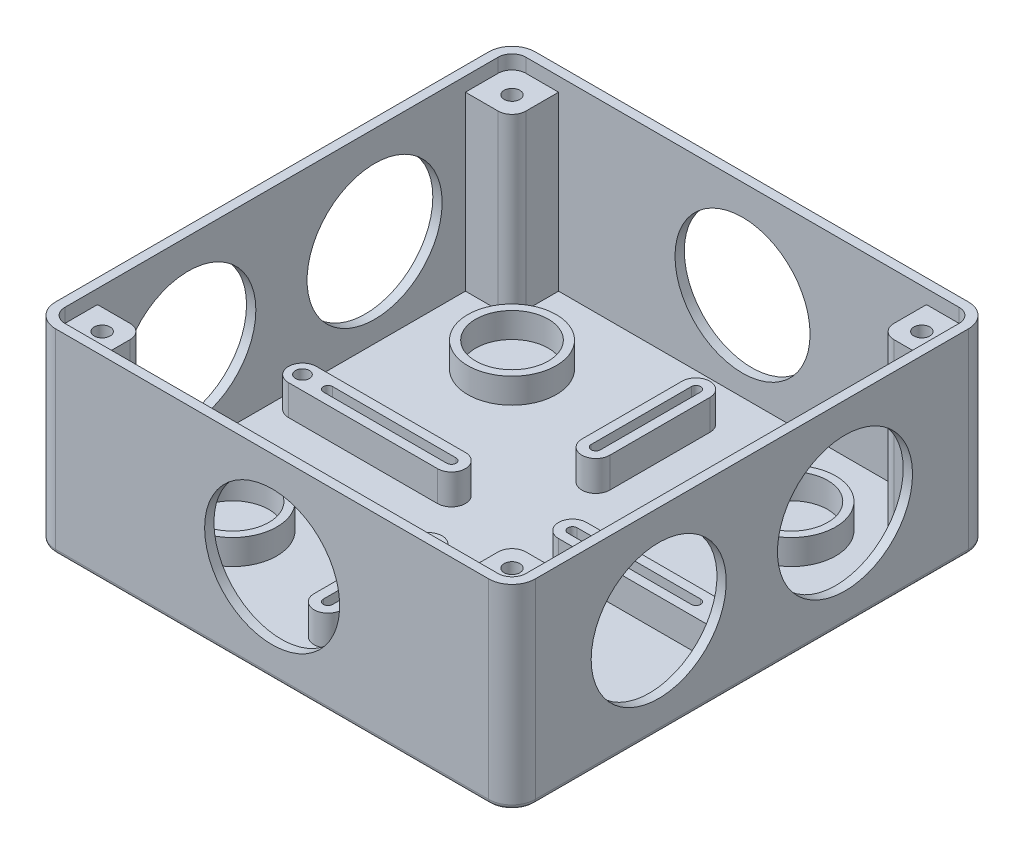
SolidWorks part; units mm, degrees
material "PBT General Purpose"
ref_plane "Front Plane" through (0, 0, 0) normal (0, 0, 1) x (1, 0, 0)
ref_plane "Top Plane" through (0, 0, 0) normal (0, 1, 0) x (1, 0, 0)
ref_plane "Right Plane" through (0, 0, 0) normal (1, 0, 0) x (0, 0, -1)
sketch "Sketch1" plane through (0, 0, 0) normal (0, 1, 0) x (1, 0, 0)
  line L0 (0, 51.5) -> (0, 0) construction
  line L1 (0, 0) -> (51.5, 0) construction
  line L2 (51.5, -46.5) -> (51.5, 46.5)
  line L3 (46.5, 51.5) -> (-46.5, 51.5)
  line L4 (-51.5, -46.5) -> (-51.5, 46.5)
  line L5 (46.5, -51.5) -> (-46.5, -51.5)
  arc A0 (51.5, 46.5) -> (46.5, 51.5) centre (46.5, 46.5) ccw
  arc A1 (-51.5, 46.5) -> (-46.5, 51.5) centre (-46.5, 46.5) cw
  arc A2 (-51.5, -46.5) -> (-46.5, -51.5) centre (-46.5, -46.5) ccw
  arc A3 (51.5, -46.5) -> (46.5, -51.5) centre (46.5, -46.5) cw
  point P17 (-51.5, 0)
  dimension "D1" = 5
  dimension "D2" = 103
  dimension "D3" = 103
extrude "Boss-Extrude1" add sketch "Sketch1" along normal blind 42
fillet "Fillet1" radius 1 8 edges at (-50.0355, 0, 50.0355) (-51.5, 0, 0) (-50.0355, 0, -50.0355) (0, 0, -51.5) (50.0355, 0, -50.0355) (51.5, 0, 0) (50.0355, 0, 50.0355) (0, 0, 51.5)
shell "Shell1" thickness 2
sketch "Sketch2" plane through (0, 0, 0) normal (0, -1, 0) x (1, 0, 0)
  line L0 (0, 64.6316) -> (0, 0) construction
  line L1 (0, 0) -> (65.5067, 0) construction
  line L2 (30, 39) -> (-30, 39)
  line L3 (30, -39) -> (-30, -39)
  line L4 (39, 30) -> (39, -30)
  line L5 (-39, 30) -> (-39, -30)
  line L6 (24.3431, 37) -> (-24.3431, 37)
  line L7 (24.3431, -37) -> (-24.3431, -37)
  line L8 (37, 24.3431) -> (37, -24.3431)
  line L9 (-37, 24.3431) -> (-37, -24.3431)
  line L11 (30, 37) -> (-30, 37) construction
  line L12 (37, 30) -> (37, -30) construction
  circle A0 centre (30, 30) radius 4
  arc A1 (39, 30) -> (30, 39) centre (30, 30) ccw
  arc A2 (24.3431, -37) -> (37, -24.3431) centre (30, -30) cw
  circle A3 centre (30, -30) radius 4
  circle A4 centre (-30, -30) radius 4
  arc A5 (-39, -30) -> (-30, -39) centre (-30, -30) ccw
  arc A6 (-24.3431, 37) -> (-37, 24.3431) centre (-30, 30) cw
  circle A7 centre (-30, 30) radius 4
  arc A8 (-39, 30) -> (-30, 39) centre (-30, 30) cw
  arc A9 (-24.3431, -37) -> (-37, -24.3431) centre (-30, -30) ccw
  arc A10 (39, -30) -> (30, -39) centre (30, -30) cw
  arc A11 (24.3431, 37) -> (37, 24.3431) centre (30, 30) ccw
  dimension "D1" = 8
  dimension "D2" = 18
  dimension "D3" = 60
  dimension "D4" = 60
  dimension "D7" = 2
  dimension "D8" = 2
  dimension "D5" = 2
  dimension "D6" = 2
extrude "Boss-Extrude2" add sketch "Sketch2" along normal blind 1.2
sketch "Sketch3" plane through (0, 0, -51.5) normal (0, 0, -1) x (-1, 0, 0)
  line L0 (0, 0) -> (0, 69.3908) construction
  line L1 (-46.5, 42) -> (46.5, 42) construction
  circle A0 centre (-42.5, 21) radius 14.5 construction
  circle A1 centre (0, 21) radius 14.5
  circle A2 centre (42.5, 21) radius 14.5 construction
  dimension "D1" = 29
  dimension "D2" = 6.5
extrude "Cut-Extrude1" cut sketch "Sketch3" against normal through all
sketch "Sketch4" plane through (0, 0, 0) normal (1, 0, 0) x (0, 0, -1)
  line L0 (0, 0) -> (0, 62.8314) construction
  line L1 (-46.5, 42) -> (46.5, 42) construction
  circle A0 centre (20, 21) radius 14.5
  circle A1 centre (-20, 21) radius 14.5
  dimension "D1" = 29
  dimension "D2" = 11
  dimension "D3" = 6.5
extrude "Cut-Extrude2" cut sketch "Sketch4" against normal through all and the other way through all
sketch "Sketch5" plane through (0, 0, 0) normal (0, -1, 0) x (1, 0, 0)
  line L0 (-22.35, 22.35) -> (22.35, 22.35)
  line L1 (-9.5, -9.5) -> (9.5, -9.5)
  line L2 (-9.5, -9.5) -> (-9.5, 9.5)
  line L3 (-9.5, 9.5) -> (9.5, 9.5)
  line L4 (9.5, -9.5) -> (9.5, 9.5)
  line L5 (-9.5, -9.5) -> (9.5, 9.5) construction
  line L6 (-9.5, 9.5) -> (9.5, -9.5) construction
  line L7 (-24.35, -24.35) -> (24.35, -24.35)
  line L8 (-24.35, -24.35) -> (-24.35, 24.35)
  line L9 (-24.35, 24.35) -> (24.35, 24.35)
  line L10 (24.35, -24.35) -> (24.35, 24.35)
  line L11 (-24.35, -24.35) -> (24.35, 24.35) construction
  line L12 (-24.35, 24.35) -> (24.35, -24.35) construction
  line L13 (22.35, -22.35) -> (22.35, 22.35)
  line L14 (-22.35, -22.35) -> (22.35, -22.35)
  line L15 (-22.35, -22.35) -> (-22.35, 22.35)
  line L16 (-7.5, 7.5) -> (7.5, 7.5)
  line L17 (7.5, -7.5) -> (7.5, 7.5)
  line L18 (-7.5, -7.5) -> (7.5, -7.5)
  line L19 (-7.5, -7.5) -> (-7.5, 7.5)
  point P0 (0, 0)
  point P6 (0, 0)
  dimension "D1" = 48.7
  dimension "D3" = 19
  dimension "D5" = 2
extrude "Boss-Extrude3" add sketch "Sketch5" along normal up to surface (1.2 mm away) contours L7 L10 L9 L8 L14 L15 L0 L13 | L1 L4 L3 L2 L18 L19 L16 L17 up to face at (-30, -1.2, 34)
sketch "Sketch6" plane through (0, -1.2, 0) normal (0, -1, 0) x (1, 0, 0)
  line L0 (7.5, 7.5) -> (27.1716, 27.1716)
  line L1 (27.1716, 27.1716) -> (30, 30) construction
  line L2 (7.5, -7.5) -> (27.1716, -27.1716)
  line L3 (27.1716, -27.1716) -> (30, -30) construction
  line L4 (0, 0) -> (0, -66.9433) construction
  line L5 (-7.5, 7.5) -> (-27.1716, 27.1716)
  line L6 (-7.5, -7.5) -> (-27.1716, -27.1716)
  circle A0 centre (30, 30) radius 4 construction
  circle A1 centre (30, -30) radius 4 construction
extrude "Extrude-Thin1" add sketch "Sketch6" against normal up to next thin contours L0
sketch "Sketch7" plane through (0, -1.2, 0) normal (0, -1, 0) x (1, 0, 0)
  line L0 (7.5, -7.5) -> (27.1716, -27.1716) construction
  line L1 (7.5, -7.5) -> (27.1716, -27.1716)
extrude "Extrude-Thin2" add sketch "Sketch7" against normal up to next thin
mirror "Mirror1" about plane through (0, 0, 0) normal (1, 0, 0) of "Extrude-Thin2", "Extrude-Thin1"
sketch "Sketch8" plane through (0, 2, 0) normal (0, 1, 0) x (1, 0, 0)
  line L0 (0, 70.5494) -> (0, 0) construction
  line L1 (0, 0) -> (92.2835, 0) construction
  circle A0 centre (30, 30) radius 9.5
  circle A1 centre (-30, 30) radius 9.5
  circle A2 centre (30, -30) radius 9.5
  circle A3 centre (-30, -30) radius 9.5
  dimension "D1" = 19
extrude "Extrude-Thin3" add sketch "Sketch8" along normal blind 5.4 thin thin type one direction reverse wall 1.7
sketch "Sketch9" plane through (0, 2, 0) normal (0, 1, 0) x (1, 0, 0)
  line L0 (-13, 3) -> (-45, 3)
  line L1 (13, 0) -> (45, 0) construction
  line L2 (-13, -3) -> (-45, -3)
  line L6 (13, 3) -> (45, 3)
  line L9 (13, -3) -> (45, -3)
  line L14 (0, 68.5135) -> (0, -74.3134) construction
  arc A0 (13, 3) -> (13, -3) centre (13, 0) ccw
  arc A1 (45, -3) -> (45, 3) centre (45, 0) ccw
  circle A2 centre (-45, 0) radius 1.5
  arc A3 (-13, 3) -> (-13, -3) centre (-13, 0) cw
  circle A4 centre (45, 0) radius 1.5
  arc A5 (-45, -3) -> (-45, 3) centre (-45, 0) cw
  point P5 (38.2798, 0)
  point P10 (21.3934, 0)
  dimension "D1" = 3
  dimension "D2" = 20
  dimension "D3" = 90
  dimension "D4" = 3
extrude "Boss-Extrude4" add sketch "Sketch9" along normal blind 6.5
sketch "Sketch10" plane through (0, 8.5, 0) normal (0, 1, 0) x (1, 0, 0)
  line L0 (13, 0) -> (39.5, 0) construction
  line L1 (13, 1) -> (39.5, 1)
  line L2 (13, -1) -> (39.5, -1)
  line L3 (0, 0) -> (0, -71.6768) construction
  line L4 (-13, 0) -> (-39.5, 0) construction
  line L5 (-13, 1) -> (-39.5, 1)
  line L6 (-13, -1) -> (-39.5, -1)
  arc A0 (13, 1) -> (13, -1) centre (13, 0) ccw
  arc A1 (39.5, -1) -> (39.5, 1) centre (39.5, 0) ccw
  circle A3 centre (45, 0) radius 1.5 construction
  arc A4 (-13, 1) -> (-13, -1) centre (-13, 0) cw
  arc A5 (-39.5, -1) -> (-39.5, 1) centre (-39.5, 0) cw
  point P4 (26.25, 0)
  point P15 (-26.25, 0)
  dimension "D1" = 1
  dimension "D2" = 3
extrude "Cut-Extrude3" cut sketch "Sketch10" against normal blind 6.5
sketch "Sketch12" plane through (0, 2, 0) normal (0, 1, 0) x (1, 0, 0)
  line L0 (39.5, 49.5) -> (39.5, 42.5)
  line L1 (46.5, 49.5) -> (-46.5, 49.5) construction
  line L2 (42.5, 39.5) -> (49.5, 39.5)
  line L3 (49.5, -46.5) -> (49.5, 46.5) construction
  line L4 (49.5, 39.5) -> (49.5, 46.5)
  line L5 (39.5, 49.5) -> (46.5, 49.5)
  line L6 (0, 69.5623) -> (0, 0) construction
  line L7 (0, 0) -> (88.4976, 0) construction
  line L8 (39.5, -49.5) -> (46.5, -49.5)
  line L9 (49.5, -39.5) -> (49.5, -46.5)
  line L10 (42.5, -39.5) -> (49.5, -39.5)
  line L11 (39.5, -49.5) -> (39.5, -42.5)
  line L12 (-39.5, -49.5) -> (-39.5, -42.5)
  line L13 (-42.5, -39.5) -> (-49.5, -39.5)
  line L14 (-49.5, -39.5) -> (-49.5, -46.5)
  line L15 (-39.5, -49.5) -> (-46.5, -49.5)
  line L16 (-39.5, 49.5) -> (-46.5, 49.5)
  line L17 (-49.5, 39.5) -> (-49.5, 46.5)
  line L18 (-42.5, 39.5) -> (-49.5, 39.5)
  line L19 (-39.5, 49.5) -> (-39.5, 42.5)
  arc A0 (49.5, 46.5) -> (46.5, 49.5) centre (46.5, 46.5) ccw construction
  arc A1 (49.5, 46.5) -> (46.5, 49.5) centre (46.5, 46.5) ccw construction
  arc A2 (49.5, 46.5) -> (46.5, 49.5) centre (46.5, 46.5) ccw
  arc A3 (39.5, 42.5) -> (42.5, 39.5) centre (42.5, 42.5) ccw
  circle A4 centre (44, 44) radius 1.7
  circle A5 centre (44, -44) radius 1.7
  arc A6 (39.5, -42.5) -> (42.5, -39.5) centre (42.5, -42.5) cw
  arc A7 (49.5, -46.5) -> (46.5, -49.5) centre (46.5, -46.5) cw
  arc A8 (-49.5, -46.5) -> (-46.5, -49.5) centre (-46.5, -46.5) ccw
  arc A9 (-39.5, -42.5) -> (-42.5, -39.5) centre (-42.5, -42.5) ccw
  circle A10 centre (-44, -44) radius 1.7
  circle A11 centre (-44, 44) radius 1.7
  arc A12 (-39.5, 42.5) -> (-42.5, 39.5) centre (-42.5, 42.5) cw
  arc A13 (-49.5, 46.5) -> (-46.5, 49.5) centre (-46.5, 46.5) cw
  dimension "D1" = 3
  dimension "D5" = 4.5
  dimension "D6" = 3.4
  dimension "D2" = 10
  dimension "D3" = 10
  dimension "D4" = 4.5
extrude "Boss-Extrude5" add sketch "Sketch12" along normal blind 37
sketch "Sketch13" plane through (0, 2, 0) normal (0, 1, 0) x (1, 0, 0)
  line L0 (0, 18) -> (0, 39.5) construction
  line L1 (0, 0) -> (83.2458, 0) construction
  line L2 (-3, 18) -> (-3, 39.5)
  line L3 (3, 18) -> (3, 39.5)
  line L4 (-1, 18) -> (-1, 39.5)
  line L5 (1, 18) -> (1, 39.5)
  line L6 (0, -18) -> (0, -39.5) construction
  line L7 (-3, -18) -> (-3, -39.5)
  line L8 (3, -18) -> (3, -39.5)
  line L9 (-1, -18) -> (-1, -39.5)
  line L10 (1, -18) -> (1, -39.5)
  arc A0 (-3, 18) -> (3, 18) centre (0, 18) ccw
  arc A1 (3, 39.5) -> (-3, 39.5) centre (0, 39.5) ccw
  arc A2 (1, 39.5) -> (-1, 39.5) centre (0, 39.5) ccw
  arc A3 (-1, 18) -> (1, 18) centre (0, 18) ccw
  arc A4 (-3, -18) -> (3, -18) centre (0, -18) cw
  arc A5 (3, -39.5) -> (-3, -39.5) centre (0, -39.5) cw
  arc A6 (-1, -18) -> (1, -18) centre (0, -18) cw
  arc A7 (1, -39.5) -> (-1, -39.5) centre (0, -39.5) cw
  point P5 (0, 28.75)
  point P18 (0, -28.75)
  dimension "D1" = 3
  dimension "D3" = 85
  dimension "D4" = 30
  dimension "D2" = 2
extrude "Boss-Extrude6" add sketch "Sketch13" along normal up to surface (6.5 mm away) up to face at (26.25, 8.5, 0)
